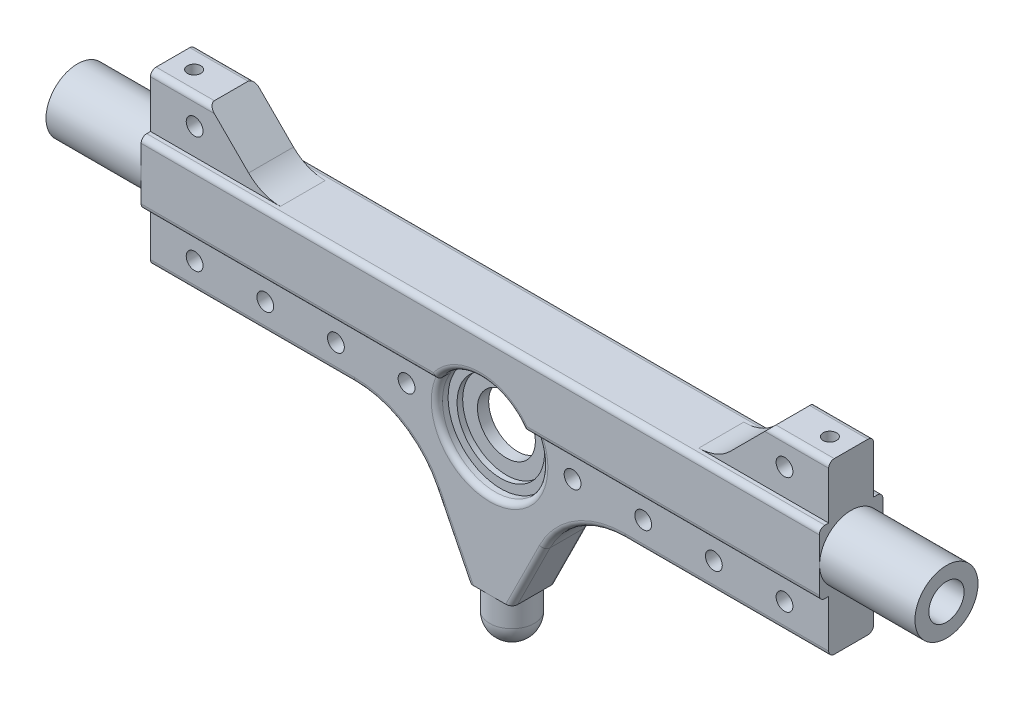
SolidWorks part; units mm, degrees
material "Cast Stainless Steel"
ref_plane "Front" through (0, 0, 0) normal (0, 0, 1) x (1, 0, 0)
ref_plane "Top" through (0, 0, 0) normal (0, 1, 0) x (1, 0, 0)
ref_plane "Right" through (0, 0, 0) normal (1, 0, 0) x (0, 0, -1)
sketch "Sketch2" plane through (0, 0, 0) normal (1, 0, 0) x (0, 0, -1)
  line L0 (-9, 18) -> (9, 18)
  line L1 (-9, 0) -> (9, 0)
  line L2 (-9, 0) -> (-9, 18)
  line L4 (9, 0) -> (9, 18)
  point P5 (0, 19.177)
  dimension "D1" = 18
  dimension "D2" = 18
extrude "Boss-Extrude2" add sketch "Sketch2" along normal mid plane 260
sketch "Sketch3" plane through (0, 0, 0) normal (0, 0, 1) x (1, 0, 0)
  line L0 (0, 0) -> (0, -47.625) construction
  line L1 (-6.35, -47.625) -> (6.35, -47.625)
  line L2 (130, 0) -> (-130, 0) construction
  line L3 (6.35, -47.625) -> (30, 0)
  line L4 (-6.35, -47.625) -> (-30, 0)
  line L5 (30, 0) -> (-30, 0)
  line L7 (-127, 0) -> (127, 0) construction
  line L8 (130, 18) -> (-130, 18) construction
  point P7 (44.831, 0)
  point P22 (0, -8.1915)
  dimension "D4" = 30
  dimension "D8" = 26.1915
  dimension "D2" = 12.7
  dimension "D3" = 44.831
  dimension "D9" = 254
extrude "Boss-Extrude3" add sketch "Sketch3" along normal mid plane 12.7
ref_plane "Plane2" through (0, -8.255, 0) normal (0, -1, 0) x (-1, 0, 0)
sketch "Sketch4" plane through (0, -8.255, 0) normal (0, -1, 0) x (-1, 0, 0)
  line L0 (-8.1915, 0) -> (8.1915, 0) construction
  line L3 (10.1534, 1.5875) -> (11.6205, 1.5875)
  line L4 (12.3825, 1.778) -> (12.3825, 2.667)
  line L5 (12.6365, 3.175) -> (14.1605, 3.175)
  line L6 (-30, 6.35) -> (30, 6.35) construction
  line L7 (-30, 6.35) -> (30, 6.35) construction
  line L8 (14.9225, 3.683) -> (14.9225, 9.0424)
  line L9 (12.3825, -1.778) -> (12.3825, -1.5875)
  line L10 (14.9225, 9.0424) -> (0, 9.0424)
  line L11 (0, 9.0424) -> (0, -9.0424)
  line L12 (14.9225, -3.683) -> (14.9225, -9.0424)
  line L13 (12.6365, -3.175) -> (14.1605, -3.175)
  line L14 (12.3825, -1.778) -> (12.3825, -2.667)
  line L15 (10.1534, -1.5875) -> (11.6205, -1.5875)
  line L16 (10.1534, 1.5875) -> (8.1915, 1.5875)
  line L17 (0, -9.0424) -> (14.9225, -9.0424)
  line L18 (11.6205, -1.5875) -> (12.3825, -1.5875)
  line L19 (14.9225, -3.683) -> (14.9225, -3.175)
  line L20 (14.9225, -3.175) -> (14.1605, -3.175)
  line L21 (11.6205, 1.5875) -> (12.3825, 1.5875)
  line L22 (12.3825, 1.5875) -> (12.3825, 1.778)
  line L23 (14.1605, 3.175) -> (14.9225, 3.175)
  line L24 (14.9225, 3.175) -> (14.9225, 3.683)
  line L27 (10.1534, -1.5875) -> (8.1915, -1.5875)
  line L29 (12.3825, -2.667) -> (12.3825, -3.175)
  line L30 (12.3825, -3.175) -> (12.6365, -3.175)
  line L31 (12.6365, 3.175) -> (12.3825, 3.175)
  line L32 (12.3825, 3.175) -> (12.3825, 2.667)
  line L33 (8.1915, 1.5875) -> (8.1915, -1.5875)
  point P14 (14.9225, 3.175)
  point P17 (12.3825, 3.175)
  point P20 (12.3825, 1.5875)
  point P49 (0, 0)
  point P50 (10.0965, -1.27)
  point P51 (12.3825, -1.5875)
  point P52 (12.3825, -3.175)
  point P53 (14.9225, -3.175)
  dimension "D1" = 12.3825
  dimension "D2" = 8.1915
  dimension "D3" = 1.5875
  dimension "D4" = 3.175
  dimension "D7" = 2.54
revolve "Cut-Revolve1" cut sketch "Sketch4" angle 360 about L11
sketch "Sketch6" plane through (130, 0, 0) normal (1, 0, 0) x (0, 0, -1)
  line L2 (-9, 0) -> (9, 0) construction
  line L7 (9, 0) -> (9, 18) construction
  circle A0 centre (0, 9) radius 5
  point P7 (0, 14)
  point P13 (5, 9)
  point P14 (9, 7.4147)
  dimension "D1" = 10
  dimension "D2" = 9
sketch "Sketch7" plane through (-130, 0, 0) normal (-1, 0, 0) x (0, 0, 1)
  circle A0 centre (0, 9) radius 8.9297
  circle A1 centre (0, 9) radius 18
  dimension "D1" = 17.8594
extrude "Cut-Extrude1" cut sketch "Sketch7" against normal blind 34
sketch "Sketch8" plane through (130, 0, 0) normal (1, 0, 0) x (0, 0, -1)
  circle A0 centre (0, 9) radius 15
  circle A1 centre (0, 9) radius 8.9297
  dimension "D1" = 30
  dimension "D2" = 17.8594
extrude "Cut-Extrude2" cut sketch "Sketch8" against normal blind 34
sketch "Sketch11" plane through (0, 0, 6.35) normal (0, 0, 1) x (1, 0, 0)
  line L0 (-30, 0) -> (-6.35, -47.625) construction
  line L1 (-96, 0) -> (-22.5512, 0)
  line L2 (-96, 0) -> (-96, -15)
  line L3 (-96, -15) -> (-22.5512, -15)
  line L4 (-22.5512, 0) -> (-22.5512, -15)
  line L5 (6.35, -47.625) -> (30, 0) construction
  line L6 (96, 0) -> (22.5512, 0)
  line L7 (96, 0) -> (96, -15)
  line L8 (96, -15) -> (22.5512, -15)
  line L9 (22.5512, 0) -> (22.5512, -15)
  line L10 (-76, 33) -> (-61, 18)
  line L11 (-96, 18) -> (-65.9033, 18)
  line L12 (-96, 18) -> (-96, 33)
  line L14 (96, 18) -> (-96, 18)
  line L20 (-96, 0) -> (-12.4313, 0)
  line L21 (12.4313, 0) -> (96, 0)
  line L27 (96, 18) -> (-96, 18)
  line L28 (96, 0) -> (96, 18)
  line L29 (96, 0) -> (96, 18)
  line L33 (-96, 0) -> (-12.4313, 0)
  line L34 (12.4313, 0) -> (96, 0)
  line L39 (-96, 33) -> (-76, 33)
  line L40 (96, 18) -> (96, 33)
  line L41 (96, 33) -> (76, 33)
  line L42 (76, 33) -> (61, 18)
  line L43 (64.5, 18) -> (79.5, 33)
  line L44 (-64.5, 18) -> (-79.5, 33)
  line L50 (-96, 18) -> (-96, 0)
  line L51 (-96, 18) -> (-96, 0)
  arc A1 (12.4313, 0) -> (-12.4313, 0) centre (0, -8.255) ccw
  arc A2 (12.4313, 0) -> (-12.4313, 0) centre (0, -8.255) ccw
  line M26 (-30, 0) -> (-6.35, -47.625)
  line M28 (6.35, -47.625) -> (30, 0)
  dimension "D2" = 15
  dimension "D3" = 15
  dimension "D4" = 45
  dimension "D5" = 15
  dimension "D6" = 15
  dimension "D7" = 20
  dimension "D8" = 45
  dimension "D9" = 20
  dimension "D10" = 16.5
  dimension "D11" = 45
  dimension "D12" = 45
  dimension "D13" = 16.5
  dimension "D1" = 0
extrude "Boss-Extrude6" add sketch "Sketch11" against normal blind 12.7 contours L2 L3 L1 M26 | L39 L12 L11 L27 L10 | L41 L42 L27 L40 | L8 L7 L6 M28
sketch "Sketch12" plane through (0, 0, 0) normal (0, 0, 1) x (1, 0, 0)
  line L0 (-6.35, -47.625) -> (6.35, -47.625) construction
  line L1 (0, -47.625) -> (6.35, -47.625)
  line L3 (6.35, -47.625) -> (6.35, -54.61)
  line L4 (0, -54.61) -> (0, -60.96) construction
  line L5 (0, -60.96) -> (0, -47.625)
  arc A0 (0, -60.96) -> (6.35, -54.61) centre (0, -54.61) ccw
  dimension "D1" = 6.985
  dimension "D2" = 6.35
revolve "Revolve2" add sketch "Sketch12" angle 360 about L4
sketch "Sketch13" plane through (0, 0, 6.35) normal (0, 0, 1) x (1, 0, 0)
  line L0 (96, -7.5) -> (66.7795, -7.5) construction
  line L1 (0, -54.5316) -> (0, 44.2934) construction
  line L2 (-96, 33) -> (-79.5, 33) construction
  line L3 (96, 18) -> (96, 33) construction
  line L4 (-96, 18) -> (-96, 33) construction
  line L9 (96, 0) -> (12.4313, 0)
  line L10 (-12.4313, 0) -> (-96, 0)
  line L11 (-96, 0) -> (-96, -15)
  line L12 (-96, -15) -> (-22.5512, -15)
  line L13 (-22.5512, -15) -> (-6.35, -47.625)
  line L14 (-6.35, -47.625) -> (0, -47.625)
  line L15 (6.35, -47.625) -> (22.5512, -15)
  line L16 (22.5512, -15) -> (96, -15)
  line L17 (96, -15) -> (96, 0)
  line L18 (96, 0) -> (12.4313, 0)
  line L19 (-12.4313, 0) -> (-96, 0)
  line L20 (-96, 0) -> (-96, -15)
  line L21 (-96, -15) -> (-22.5512, -15)
  line L22 (-22.5512, -15) -> (-6.35, -47.625)
  line L23 (-6.35, -47.625) -> (0, -47.625)
  line L24 (6.35, -47.625) -> (22.5512, -15)
  line L25 (22.5512, -15) -> (96, -15)
  line L26 (96, -15) -> (96, 0)
  line L31 (0, -47.625) -> (6.35, -47.625)
  line L32 (0, -47.625) -> (6.35, -47.625)
  circle A0 centre (83.5, -7.5) radius 2.3813
  circle A1 centre (63.5, -7.5) radius 2.3813
  arc A2 (-12.4313, 0) -> (12.4313, 0) centre (0, -8.255) ccw
  arc A3 (-12.4313, 0) -> (12.4313, 0) centre (0, -8.255) ccw
  circle A4 centre (43.5, -7.5) radius 2.3812
  circle A5 centre (23.5, -7.5) radius 2.3812
  circle A6 centre (-83.5, -7.5) radius 2.3813
  circle A7 centre (-63.5, -7.5) radius 2.3813
  circle A8 centre (-43.5, -7.5) radius 2.3812
  circle A9 centre (-23.5, -7.5) radius 2.3812
  circle A10 centre (-83.5, 25.5) radius 2.3813
  circle A11 centre (83.5, 25.5) radius 2.3813
  dimension "D3" = 4.7625
  dimension "D6" = 4.7625
  dimension "D7" = 12.5
  dimension "D9" = 4.7625
  dimension "D10" = 4.7625
  dimension "D2" = 12.5
  dimension "D5" = 7.5
  dimension "D8" = 12.5
  dimension "D11" = 167
  dimension "D1" = 0
  dimension "D4" = 4
extrude "Cut-Extrude3" cut sketch "Sketch13" against normal blind 14.27 contours A11 | A0 | A1 | A4 | A5 | A6 | A7 | A8 | A9 | A10
fillet "Fillet4" radius 25.4 2 edges at (22.5512, -15, 0) (-22.5512, -15, 0)
extrude "Cut-Extrude4" cut sketch "Sketch6" against normal blind 42
sketch "Sketch14" plane through (88, 0, 0) normal (1, 0, 0) x (0, 0, -1)
  circle A0 centre (0, 9) radius 3.9688
  dimension "D1" = 7.9375
extrude "Cut-Extrude5" cut sketch "Sketch14" against normal blind 22
sketch "Sketch15" plane through (130, 0, 0) normal (1, 0, 0) x (0, 0, -1)
  circle A0 centre (0, 9) radius 5 construction
  circle A1 centre (0, 9) radius 8.9297
  circle A2 centre (0, 9) radius 8.9297
  circle A3 centre (0, 9) radius 5
  dimension "D1" = 0
extrude "Cut-Extrude6" cut sketch "Sketch15" against normal blind 7
sketch "Sketch16" plane through (0, -15, 0) normal (0, -1, 0) x (1, 0, 0)
  line L0 (96, -6.35) -> (96, 6.35) construction
  circle A0 centre (90, 0) radius 1.905
  dimension "D2" = 3.81
  dimension "D1" = 6
extrude "Cut-Extrude7" cut sketch "Sketch16" against normal through all
ref_plane "Plane3" through (0, 0, 0) normal (-1, 0, 0) x (0, 0, 1)
mirror "Mirror1" about plane through (0, 0, 0) normal (-1, 0, 0) of "Cut-Extrude7", "Cut-Extrude5", "Cut-Extrude4", "Cut-Extrude6"
fillet "Fillet5" radius 12.7 2 edges at (64.5, 18, 0) (-64.5, 18, 0)
fillet "Fillet7" radius 1.5875 16 edges at (10.9489, -38.364, -6.35) (10.9489, -38.364, 6.35) (24.9142, -18.8117, -6.35) (24.9142, -18.8117, 6.35) (-10.9489, -38.364, 6.35) (-10.9489, -38.364, -6.35) (-24.9142, -18.8117, -6.35) (-24.9142, -18.8117, 6.35) (87.75, 33, 6.35) (87.75, 33, -6.35) (67.1486, -15, 6.35) (67.1486, -15, -6.35) (-67.1486, -15, 6.35) (-67.1486, -15, -6.35) (-87.75, 33, 6.35) (-87.75, 33, -6.35)
fillet "Fillet8" radius 1.5875 10 edges at (54.2156, 0, -9) (-54.2156, 0, -9) (0, 18, -9) (-54.2156, 0, 9) (54.2156, 0, 9) (0, 18, 9) (0, 6.6675, 9) (0, -23.1775, 6.35) (0, 6.6675, -9) (0, -23.1775, -6.35)
sketch "Sketch18" plane through (0, 0, 9) normal (0, 0, 1) x (1, 0, 0)
  line L55 (-98.54, 20.54) -> (-98.54, 31.4125)
  line L56 (-98.54, 35.54) -> (-98.54, 31.4125)
  line L57 (-98.54, 35.54) -> (-78.4479, 35.54)
  line L58 (-76.1164, 33.2086) -> (-78.4479, 35.54)
  line L59 (-66.4237, 23.5158) -> (-76.1164, 33.2086)
  line L60 (-59.2395, 20.54) -> (59.2395, 20.54)
  line L61 (66.4237, 23.5158) -> (76.1164, 33.2086)
  line L62 (78.4479, 35.54) -> (76.1164, 33.2086)
  line L63 (78.4479, 35.54) -> (98.54, 35.54)
  line L64 (98.54, 31.4125) -> (98.54, 35.54)
  line L65 (98.54, 20.54) -> (98.54, 31.4125)
  line L66 (125.54, 20.54) -> (98.54, 20.54)
  line L67 (125.54, -2.54) -> (125.54, 20.54)
  line L68 (98.54, -2.54) -> (125.54, -2.54)
  line L69 (98.54, -2.54) -> (98.54, -13.4125)
  line L70 (98.54, -17.54) -> (98.54, -13.4125)
  line L71 (98.54, -17.54) -> (38.2973, -17.54)
  line L72 (17.8228, -30.2326) -> (8.89, -48.2209)
  line L73 (8.89, -54.61) -> (8.89, -48.2209)
  line L74 (-8.89, -48.2209) -> (-8.89, -54.61)
  line L75 (-8.89, -48.2209) -> (-17.8228, -30.2326)
  line L76 (-38.2973, -17.54) -> (-98.54, -17.54)
  line L77 (-98.54, -13.4125) -> (-98.54, -17.54)
  line L78 (-98.54, -2.54) -> (-98.54, -13.4125)
  line L79 (-125.54, -2.54) -> (-98.54, -2.54)
  line L80 (-125.54, 20.54) -> (-125.54, -2.54)
  line L81 (-98.54, 20.54) -> (-125.54, 20.54)
  arc A10 (-66.4237, 23.5158) -> (-59.2395, 20.54) centre (-59.2395, 30.7) ccw
  arc A11 (59.2395, 20.54) -> (66.4237, 23.5158) centre (59.2395, 30.7) ccw
  arc A12 (38.2973, -17.54) -> (17.8228, -30.2326) centre (38.2973, -40.4) ccw
  arc A13 (-8.89, -54.61) -> (8.89, -54.61) centre (0, -54.61) ccw
  arc A14 (-17.8228, -30.2326) -> (-38.2973, -17.54) centre (-38.2973, -40.4) ccw
sketch "Sketch19" [suppressed] plane through (0, -15, 0) normal (0, -1, 0) x (1, 0, 0)
  line L0 (-96, -4.7625) -> (-96, 4.7625) construction
  line L1 (-62.98, -0.9525) -> (-70.6, -0.9525)
  line L2 (-62.98, -0.9525) -> (-62.98, 0.9525)
  line L3 (-62.98, 0.9525) -> (-70.6, 0.9525)
  line L4 (-70.6, -0.9525) -> (-70.6, 0.9525)
  line L5 (-96, -4.7625) -> (-38.2973, -4.7625) construction
  line L6 (-38.2973, 4.7625) -> (-96, 4.7625) construction
  dimension "D1" = 25.4
  dimension "D2" = 3.81
  dimension "D3" = 3.81
  dimension "D4" = 7.62
extrude "Boss-Extrude7" [suppressed] add sketch "Sketch19" along normal blind 25.4
sketch "Sketch20" [suppressed] plane through (-24.0655, -11.9506, 0) normal (-0.8956, -0.4448, 0) x (0, 0, 1)
  line L0 (-4.7625, -19.1507) -> (-4.7625, -39.8309) construction
  line L1 (-0.9525, -32.2109) -> (0.9525, -32.2109)
  line L2 (-0.9525, -32.2109) -> (-0.9525, -24.5909)
  line L3 (-0.9525, -24.5909) -> (0.9525, -24.5909)
  line L4 (0.9525, -32.2109) -> (0.9525, -24.5909)
  line L5 (4.7625, -39.8309) -> (4.7625, -19.1507) construction
  line L6 (4.7625, -39.8309) -> (0, -39.8309) construction
  dimension "D1" = 3.81
  dimension "D2" = 3.81
  dimension "D3" = 7.62
  dimension "D4" = 7.62
extrude "Boss-Extrude8" [suppressed] add sketch "Sketch20" along normal blind 25.4
sketch "Sketch21" [suppressed] plane through (0, 18, 0) normal (0, 1, 0) x (1, 0, 0)
  line L0 (-59.2395, 6.35) -> (-59.2395, -6.35) construction
  line L1 (-49.0795, 1.6975) -> (-41.4595, 1.6975)
  line L2 (-49.0795, 1.6975) -> (-49.0795, -1.6975)
  line L3 (-49.0795, -1.6975) -> (-41.4595, -1.6975)
  line L4 (-41.4595, 1.6975) -> (-41.4595, -1.6975)
  line L5 (-96, -7.4125) -> (96, -7.4125) construction
  line L6 (96, 7.4125) -> (-96, 7.4125) construction
  dimension "D1" = 7.62
  dimension "D2" = 10.16
  dimension "D3" = 5.715
  dimension "D4" = 5.715
extrude "Boss-Extrude9" [suppressed] add sketch "Sketch21" along normal blind 25.4
sketch "Sketch22" [suppressed] plane through (0, 18, 0) normal (0, 1, 0) x (1, 0, 0)
  line L0 (-41.4595, 1.6975) -> (-49.0795, 1.6975) construction
  line L1 (-3.81, 1.6975) -> (3.81, 1.6975)
  line L2 (-3.81, 1.6975) -> (-3.81, -1.6975)
  line L3 (-3.81, -1.6975) -> (3.81, -1.6975)
  line L4 (3.81, 1.6975) -> (3.81, -1.6975)
  line L5 (-49.0795, -1.6975) -> (-41.4595, -1.6975) construction
  line L6 (96, 7.4125) -> (-96, 7.4125) construction
  point P8 (0, 7.4125)
  dimension "D1" = 7.62
  dimension "D2" = 0
  dimension "D3" = 0
  dimension "D4" = 3.81
extrude "Boss-Extrude10" [suppressed] add sketch "Sketch22" along normal blind 25.4
fillet "Fillet12" [suppressed] radius 6.35
mirror "Mirror2" [suppressed] about plane through (0, 0, 0) normal (-1, 0, 0)
fillet "Fillet13" [suppressed] radius 6.35
sketch "Sketch23" [suppressed] plane through (0, 0, -9) normal (0, 0, -1) x (-1, 0, 0)
  line L0 (98.54, 20.54) -> (98.54, -2.54)
  line L1 (-98.54, 20.54) -> (-98.54, -2.54)
  line L27 (8.89, -54.61) -> (8.89, -48.2209)
  line L28 (-8.89, -48.2209) -> (-8.89, -54.61)
  line L29 (-17.8228, -30.2326) -> (-8.89, -48.2209)
  line L30 (-98.54, -17.54) -> (-38.2973, -17.54)
  line L31 (-98.54, -13.4125) -> (-98.54, -17.54)
  line L32 (-98.54, -2.54) -> (-98.54, -13.4125)
  line L33 (-125.54, -2.54) -> (-98.54, -2.54)
  line L34 (-125.54, 20.54) -> (-125.54, -2.54)
  line L35 (-98.54, 20.54) -> (-125.54, 20.54)
  line L36 (-98.54, 31.4125) -> (-98.54, 20.54)
  line L37 (-98.54, 35.54) -> (-98.54, 31.4125)
  line L38 (-78.4479, 35.54) -> (-98.54, 35.54)
  line L39 (-76.1164, 33.2086) -> (-78.4479, 35.54)
  line L40 (-66.4237, 23.5158) -> (-76.1164, 33.2086)
  line L41 (59.2395, 20.54) -> (-59.2395, 20.54)
  line L42 (76.1164, 33.2086) -> (66.4237, 23.5158)
  line L43 (78.4479, 35.54) -> (76.1164, 33.2086)
  line L44 (98.54, 35.54) -> (78.4479, 35.54)
  line L45 (98.54, 31.4125) -> (98.54, 35.54)
  line L46 (98.54, 20.54) -> (98.54, 31.4125)
  line L47 (125.54, 20.54) -> (98.54, 20.54)
  line L48 (125.54, -2.54) -> (125.54, 20.54)
  line L49 (98.54, -2.54) -> (125.54, -2.54)
  line L50 (98.54, -13.4125) -> (98.54, -2.54)
  line L51 (98.54, -17.54) -> (98.54, -13.4125)
  line L52 (38.2973, -17.54) -> (98.54, -17.54)
  line L53 (8.89, -48.2209) -> (17.8228, -30.2326)
  line L54 (8.89, -54.61) -> (8.89, -48.2209)
  line L55 (-8.89, -48.2209) -> (-8.89, -54.61)
  line L56 (-17.8228, -30.2326) -> (-8.89, -48.2209)
  line L57 (-98.54, -17.54) -> (-38.2973, -17.54)
  line L58 (-98.54, -13.4125) -> (-98.54, -17.54)
  line L59 (-98.54, -2.54) -> (-98.54, -13.4125)
  line L63 (-98.54, 31.4125) -> (-98.54, 20.54)
  line L64 (-98.54, 35.54) -> (-98.54, 31.4125)
  line L65 (-78.4479, 35.54) -> (-98.54, 35.54)
  line L66 (-76.1164, 33.2086) -> (-78.4479, 35.54)
  line L67 (-66.4237, 23.5158) -> (-76.1164, 33.2086)
  line L68 (59.2395, 20.54) -> (-59.2395, 20.54)
  line L69 (76.1164, 33.2086) -> (66.4237, 23.5158)
  line L70 (78.4479, 35.54) -> (76.1164, 33.2086)
  line L71 (98.54, 35.54) -> (78.4479, 35.54)
  line L72 (98.54, 31.4125) -> (98.54, 35.54)
  line L73 (98.54, 20.54) -> (98.54, 31.4125)
  line L77 (98.54, -13.4125) -> (98.54, -2.54)
  line L78 (98.54, -17.54) -> (98.54, -13.4125)
  line L79 (38.2973, -17.54) -> (98.54, -17.54)
  line L80 (8.89, -48.2209) -> (17.8228, -30.2326)
  arc A5 (-8.89, -54.61) -> (8.89, -54.61) centre (0, -54.61) ccw
  arc A6 (-17.8228, -30.2326) -> (-38.2973, -17.54) centre (-38.2973, -40.4) ccw
  arc A7 (-66.4237, 23.5158) -> (-59.2395, 20.54) centre (-59.2395, 30.7) ccw
  arc A8 (59.2395, 20.54) -> (66.4237, 23.5158) centre (59.2395, 30.7) ccw
  arc A9 (38.2973, -17.54) -> (17.8228, -30.2326) centre (38.2973, -40.4) ccw
  arc A10 (-8.89, -54.61) -> (8.89, -54.61) centre (0, -54.61) ccw
  arc A11 (-17.8228, -30.2326) -> (-38.2973, -17.54) centre (-38.2973, -40.4) ccw
  arc A12 (-66.4237, 23.5158) -> (-59.2395, 20.54) centre (-59.2395, 30.7) ccw
  arc A13 (59.2395, 20.54) -> (66.4237, 23.5158) centre (59.2395, 30.7) ccw
  arc A14 (38.2973, -17.54) -> (17.8228, -30.2326) centre (38.2973, -40.4) ccw
  dimension "D1" = 0
sketch "Sketch24" plane through (0, 0, -6.35) normal (0, 0, -1) x (-1, 0, 0)
  point P0 (-83.5, -7.5)
fillet "Fillet14" [suppressed] radius 1.5875
sketch "Sketch25" [suppressed] plane through (0, 43.4, 0) normal (0, 1, 0) x (1, 0, 0)
  point P0 (-45.1971, 0)
  point P1 (0, 0)
  dimension "D1" = 45.1971
sketch "Sketch26" [suppressed] plane through (0, 0, -9) normal (0, 0, -1) x (-1, 0, 0)
  line L0 (123, 0.0703) -> (123, 17.9297) construction
  line L1 (123, 0.0703) -> (123, 17.9297)
  line L2 (-123, 17.9297) -> (-123, 0.0703) construction
  line L3 (-123, 17.9297) -> (-123, 0.0703)
  circle A0 centre (83.5, -7.5) radius 2.3813 construction
  circle A1 centre (83.5, -7.5) radius 2.3813
  circle A2 centre (-83.5, -7.5) radius 2.3813 construction
  circle A3 centre (-83.5, -7.5) radius 2.3813
  arc A4 (-6.35, -54.61) -> (6.35, -54.61) centre (0, -54.61) ccw construction
  arc A5 (-6.35, -54.61) -> (6.35, -54.61) centre (0, -54.61) ccw
  point P13 (0, -60.96)
  dimension "D1" = 39.5
  dimension "D2" = 246
  dimension "D3" = 53.46
sketch "Sketch27" plane through (0, 33, 0) normal (0, 1, 0) x (1, 0, 0)
  line L0 (88, -3.9688) -> (88, 3.9688) construction
  line L1 (88, -3.9688) -> (88, 3.9688)
  line L2 (123, -5) -> (123, 5) construction
  line L3 (123, -5) -> (123, 5)
  line L4 (66, -3.9688) -> (66, 3.9688) construction
  line L5 (66, -3.9688) -> (66, 3.9688)
  line L6 (96, 4.7625) -> (96, -4.7625) construction
  line L7 (96, 4.7625) -> (96, -4.7625)
  dimension "D1" = 27
  dimension "D2" = 10
  dimension "D3" = 35
  dimension "D4" = 7.9375
  dimension "D5" = 57
equation "\"0.0625mmin\"=0.0625"
equation "\".25i\"=0.1"
